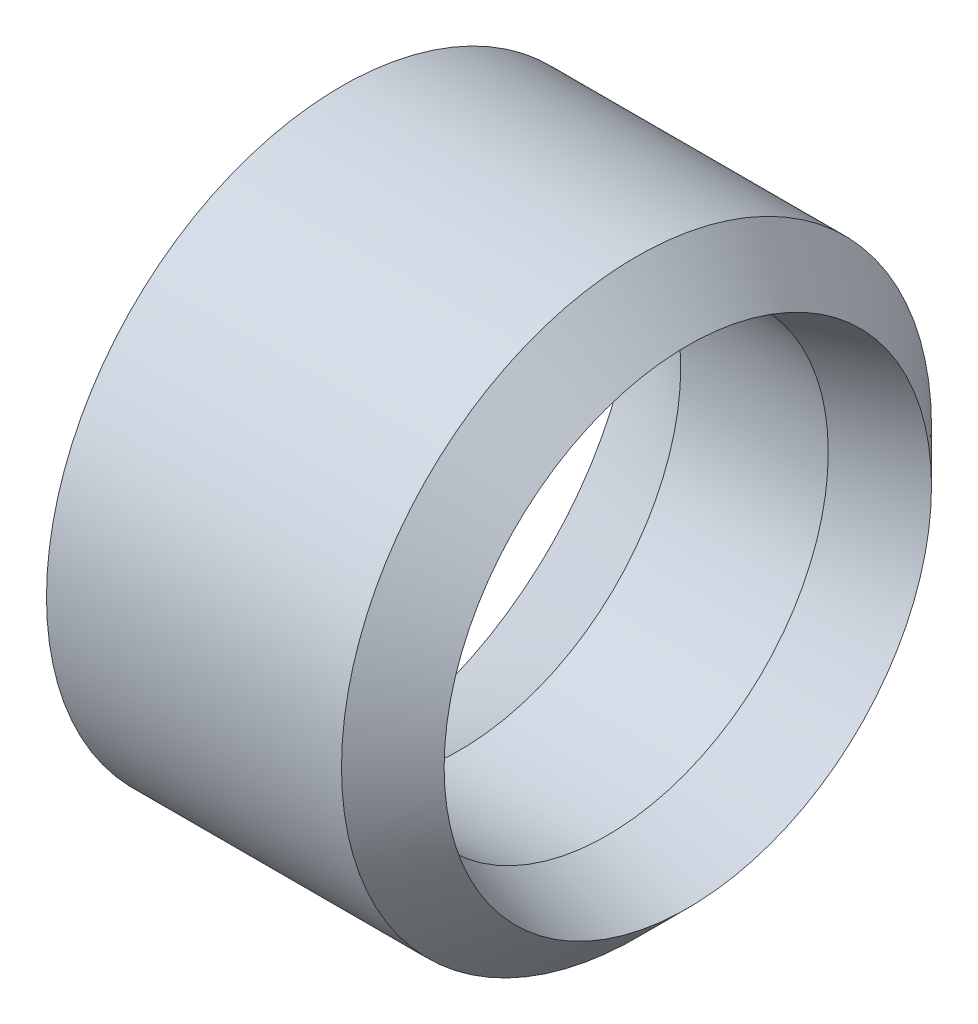
SolidWorks part; units mm, degrees
material "C (Graphite)"
ref_plane "Front Plane" through (0, 0, 0) normal (0, 0, 1) x (1, 0, 0)
ref_plane "Top Plane" through (0, 0, 0) normal (0, 1, 0) x (1, 0, 0)
ref_plane "Right Plane" through (0, 0, 0) normal (1, 0, 0) x (0, 0, -1)
sketch "Sketch2" plane through (0, 0, 0) normal (0, 0, 1) x (1, 0, 0)
  line L0 (0, 0) -> (0, 19.05) construction
  line L11 (0, 19.05) -> (-20.32, 31.75)
  line L12 (81.28, 0) -> (81.28, 38.1) construction
  line L13 (-20.32, 44.45) -> (-7.62, 44.45)
  line L14 (-20.32, 44.45) -> (-20.32, 41.529)
  line L15 (-20.32, 41.529) -> (-7.62, 41.529)
  line L16 (-7.62, 41.529) -> (-7.62, 44.45)
  line L17 (-17.78, 41.529) -> (-17.78, 34.417)
  line L18 (-10.16, 25.4) -> (15.24, 25.4)
  line L22 (-20.32, 31.75) -> (-20.32, 44.45)
  line L23 (0, 0) -> (81.28, 0) construction
  line L25 (19.6574, 20.9826) -> (15.24, 25.4)
  line L27 (-20.32, 44.45) -> (0, 44.45)
  line L28 (-17.78, 34.417) -> (-10.668, 34.417)
  line L29 (-10.668, 34.417) -> (-10.668, 41.529)
  line L30 (81.28, 44.45) -> (0, 44.45)
  line L36 (-1.27, 44.45) -> (2.54, 44.45)
  line L37 (-1.27, 44.45) -> (-1.27, 40.64)
  line L38 (-1.27, 40.64) -> (2.54, 40.64)
  line L39 (2.54, 44.45) -> (2.54, 40.64)
  line L40 (0, 19.05) -> (12.7, 19.05)
  line L43 (81.28, 44.45) -> (81.28, 38.1)
  line L44 (12.7, 19.05) -> (81.28, 38.1)
  line L45 (-12.192, 26.67) -> (15.7661, 26.67)
  line L46 (15.7661, 26.67) -> (21.063, 21.3731)
  dimension "D1" = 19.05
  dimension "D2" = 20.32
  dimension "D4" = 45
  dimension "D5" = 31.75
  dimension "D15" = 25.4
  dimension "D3" = 12.7
  dimension "D6" = 68.58
  dimension "D7" = 38.1
  dimension "D8" = 41.529
  dimension "D9" = 7.112
  dimension "D10" = 7.112
  dimension "D11" = 2.54
  dimension "D12" = 6.35
  dimension "D13" = 3.81
  dimension "D14" = 3.81
  dimension "D16" = 12.7
  dimension "D18" = 1.27
  dimension "D19" = 44.45
  dimension "D20" = 1.27
  dimension "D17" = 25.4
  dimension "D21" = 34.417
revolve "Revolve2" add sketch "Sketch2" angle 360 about L23
